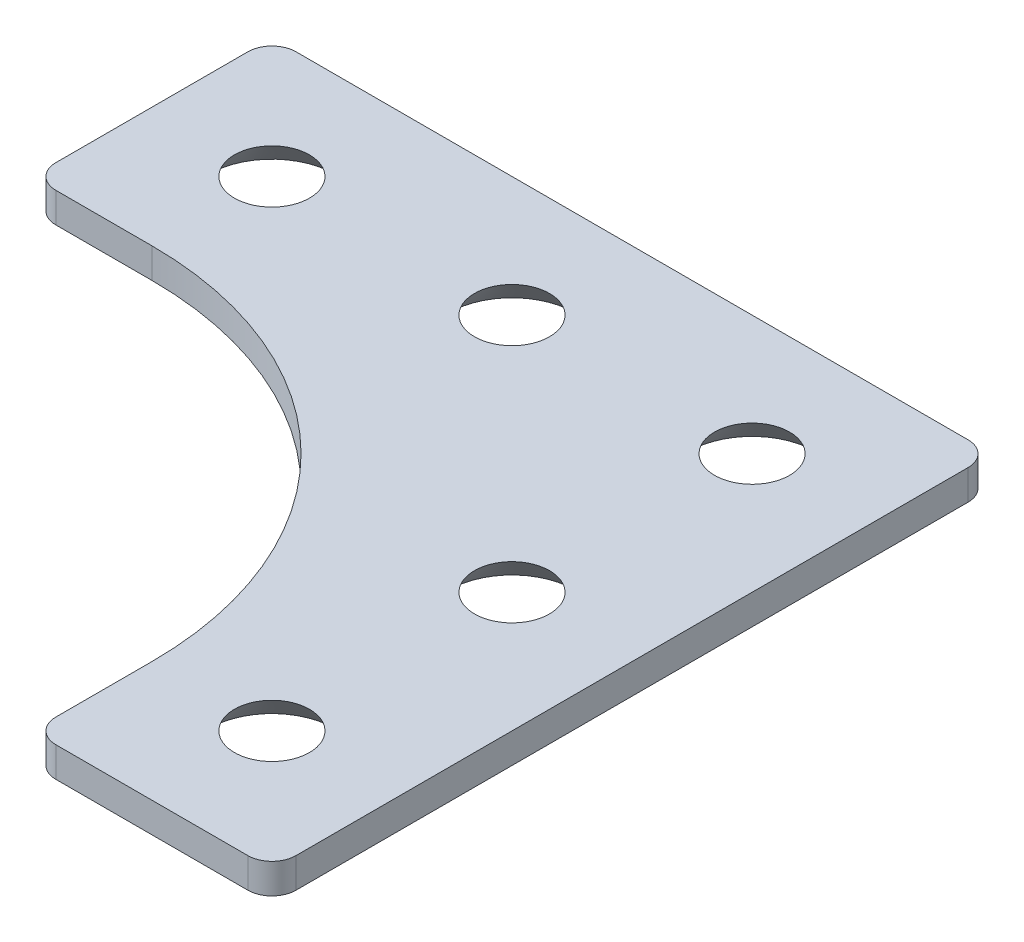
SolidWorks part; units mm, degrees
ref_plane "Front Plane" through (0, 0, 0) normal (0, 0, 1) x (1, 0, 0)
ref_plane "Top Plane" through (0, 0, 0) normal (0, 1, 0) x (1, 0, 0)
ref_plane "Right Plane" through (0, 0, 0) normal (1, 0, 0) x (0, 0, -1)
sketch "Sketch1" plane through (0, 0, 0) normal (0, 1, 0) x (1, 0, 0)
  line L0 (274.8938, 269.2112) -> (203.7738, 269.2112)
  line L1 (274.8938, 269.2112) -> (178.3738, 269.2112) construction
  line L2 (201.2338, 266.6712) -> (201.2338, 246.3512)
  line L3 (178.3738, 243.8112) -> (213.9338, 243.8112) construction
  line L4 (203.7738, 243.8112) -> (213.9338, 243.8112)
  line L5 (252.0338, 269.2112) -> (252.0338, -416.5888) construction
  line L6 (252.0338, 205.7112) -> (252.0338, 195.5512)
  line L7 (252.0338, 205.7112) -> (252.0338, 170.1512) construction
  line L8 (254.5738, 193.0112) -> (274.8938, 193.0112)
  line L9 (277.4338, 170.1512) -> (277.4338, 266.6712) construction
  line L10 (277.4338, 195.5512) -> (277.4338, 266.6712)
  arc A0 (274.8938, 269.2112) -> (277.4338, 266.6712) centre (274.8938, 266.6712) cw
  arc A1 (201.2338, 266.6712) -> (203.7738, 269.2112) centre (203.7738, 266.6712) cw
  arc A2 (203.7738, 243.8112) -> (201.2338, 246.3512) centre (203.7738, 246.3512) cw
  arc A3 (254.5738, 193.0112) -> (252.0338, 195.5512) centre (254.5738, 195.5512) cw
  arc A4 (277.4338, 195.5512) -> (274.8938, 193.0112) centre (274.8938, 195.5512) cw
  arc A5 (252.0338, 205.7112) -> (213.9338, 243.8112) centre (213.9338, 205.7112) ccw
  point P20 (277.4338, 269.2112)
  point P23 (201.2338, 269.2112)
  point P26 (201.2338, 243.8112)
  point P29 (252.0338, 193.0112)
  point P32 (277.4338, 193.0112)
  point P35 (252.0338, 243.8112)
  dimension "D1" = 2.54
  dimension "D2" = 2.54
  dimension "D3" = 2.54
  dimension "D4" = 2.54
  dimension "D5" = 2.54
  dimension "D6" = 38.1
extrude "Boss-Extrude1" add sketch "Sketch1" along normal blind 3.175
sketch "Sketch2" plane through (0, 3.175, 0) normal (0, 1, 0) x (1, 0, 0)
  line L0 (213.9338, 256.5112) -> (239.3338, 256.5112)
  line L1 (239.3338, 256.5112) -> (264.7338, 256.5112)
  line L2 (264.7338, 256.5112) -> (264.7338, 231.1112)
  line L3 (264.7338, 231.1112) -> (264.7338, 205.7112)
hole_wizard "1/4 (0.25) Diameter Hole1" positions "Sketch3" profile "Sketch4" hole size "1/4" standard "ANSI Inch" end condition through all
sketch "Sketch3" plane through (0, 0, 0) normal (0, -1, 0) x (-1, 0, 0)
  point P0 (-264.7338, 205.7112)
  point P3 (-264.7338, 231.1112)
  point P6 (-264.7338, 256.5112)
  point P9 (-239.3338, 256.5112)
  point P12 (-213.9338, 256.5112)
sketch "Sketch4" plane through (264.7338, 0, -205.7112) normal (1, 0, 0) x (0, 0, -1)
  line L0 (0, 0) -> (0, 3.175)
  line L1 (0, 3.175) -> (3.175, 3.175)
  line L2 (3.175, 3.175) -> (3.175, 4.0907)
  line L3 (3.175, 4.0907) -> (6.731, 0)
  line L5 (6.731, 0) -> (0, 0)
  line L6 (-3.175, 4.0907) -> (-6.731, 0) construction
  line L11 (0, -6.35) -> (0, 107.95) construction
  dimension "Thru Hole Dia." = 6.35
  dimension "Thru Hole Depth" = 3.175
  dimension "Near C'Sink Dia." = 13.462
  dimension "Near C'Sink Angle" = 82
